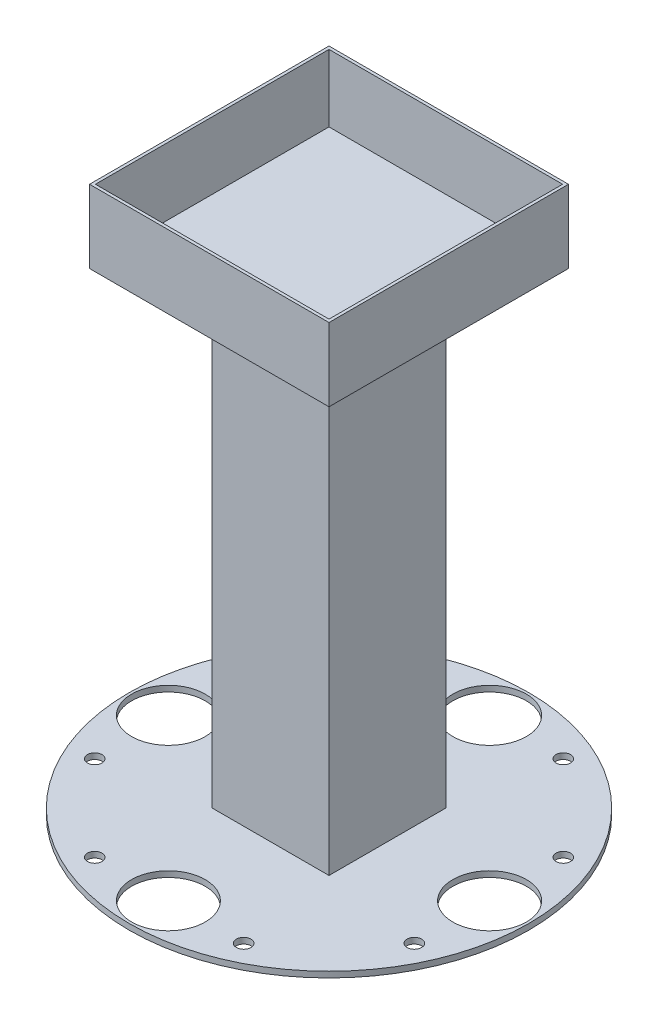
SolidWorks part; units mm, degrees
ref_plane "Front Plane" through (0, 0, 0) normal (0, 0, 1) x (1, 0, 0)
ref_plane "Top Plane" through (0, 0, 0) normal (0, 1, 0) x (1, 0, 0)
ref_plane "Right Plane" through (0, 0, 0) normal (1, 0, 0) x (0, 0, -1)
sketch "Sketch1" plane through (0, 0, 0) normal (0, 1, 0) x (1, 0, 0)
  circle A0 centre (0, 0) radius 86.9315
extrude "Boss-Extrude1" add sketch "Sketch1" along normal blind 2.54
sketch "Sketch2" plane through (0, 2.54, 0) normal (0, 1, 0) x (1, 0, 0)
  line L1 (-25.4, 25.4) -> (25.4, 25.4)
  line L2 (-25.4, 25.4) -> (-25.4, -25.4)
  line L3 (-25.4, -25.4) -> (25.4, -25.4)
  line L4 (25.4, 25.4) -> (25.4, -25.4)
  line L5 (-25.4, 25.4) -> (25.4, -25.4) construction
  line L6 (-25.4, -25.4) -> (25.4, 25.4) construction
  point P0 (0, 0)
extrude "Boss-Extrude2" add sketch "Sketch2" along normal blind 203.2
sketch "Sketch3" plane through (0, 2.54, 0) normal (0, 1, 0) x (1, 0, 0)
  line L0 (0, 86.9315) -> (0, -86.9315) construction
  line L1 (86.9315, 0) -> (-86.9315, 0)
  circle A1 centre (-32.385, 69.5007) radius 3.175
  circle A2 centre (32.385, 69.5007) radius 3.175
  circle A3 centre (69.5007, 32.385) radius 3.175
  circle A4 centre (69.5007, -32.385) radius 3.175
  circle A5 centre (32.385, -69.5007) radius 3.175
  circle A6 centre (-32.385, -69.5007) radius 3.175
  circle A7 centre (-69.5007, -32.385) radius 3.175
  circle A8 centre (-69.5007, 32.385) radius 3.175
  circle A9 centre (0, 0) radius 86.9315 construction
  point P15 (0, 0)
extrude "Cut-Extrude1" cut sketch "Sketch3" against normal blind 203.2 contours A5 | A4 | A3 | A2 | A1 | A8 | A7 | A6
sketch "Sketch4" plane through (0, 205.74, 0) normal (0, 1, 0) x (1, 0, 0)
  line L1 (-52.07, 52.07) -> (52.07, 52.07)
  line L2 (-52.07, 52.07) -> (-52.07, -52.07)
  line L3 (-52.07, -52.07) -> (52.07, -52.07)
  line L4 (52.07, 52.07) -> (52.07, -52.07)
  line L5 (-52.07, 52.07) -> (52.07, -52.07) construction
  line L6 (-52.07, -52.07) -> (52.07, 52.07) construction
  point P0 (0, 0)
extrude "Boss-Extrude3" add sketch "Sketch4" along normal blind 31.75
sketch "Sketch5" plane through (0, 237.49, 0) normal (0, 1, 0) x (1, 0, 0)
  line L1 (-50.8, 50.8) -> (50.8, 50.8)
  line L2 (-50.8, 50.8) -> (-50.8, -50.8)
  line L3 (-50.8, -50.8) -> (50.8, -50.8)
  line L4 (50.8, 50.8) -> (50.8, -50.8)
  line L5 (-50.8, 50.8) -> (50.8, -50.8) construction
  line L6 (-50.8, -50.8) -> (50.8, 50.8) construction
  point P0 (0, 0)
extrude "Cut-Extrude2" cut sketch "Sketch5" against normal blind 29.21
sketch "Sketch9" plane through (0, 2.54, 0) normal (0, 1, 0) x (1, 0, 0)
  line L0 (52.07, 0) -> (69.85, 0)
  line L1 (52.07, -52.07) -> (52.07, 52.07) construction
  circle A0 centre (69.85, 0) radius 16.002
  dimension "D2" = 32.004
  dimension "D1" = 17.78
extrude "Cut-Extrude3" cut sketch "Sketch9" against normal through all contours A0
pattern_circular "CirPattern1" count 4 over 360 about axis through (0, 0, 0) along (0, 1, 0) of "Cut-Extrude3"
